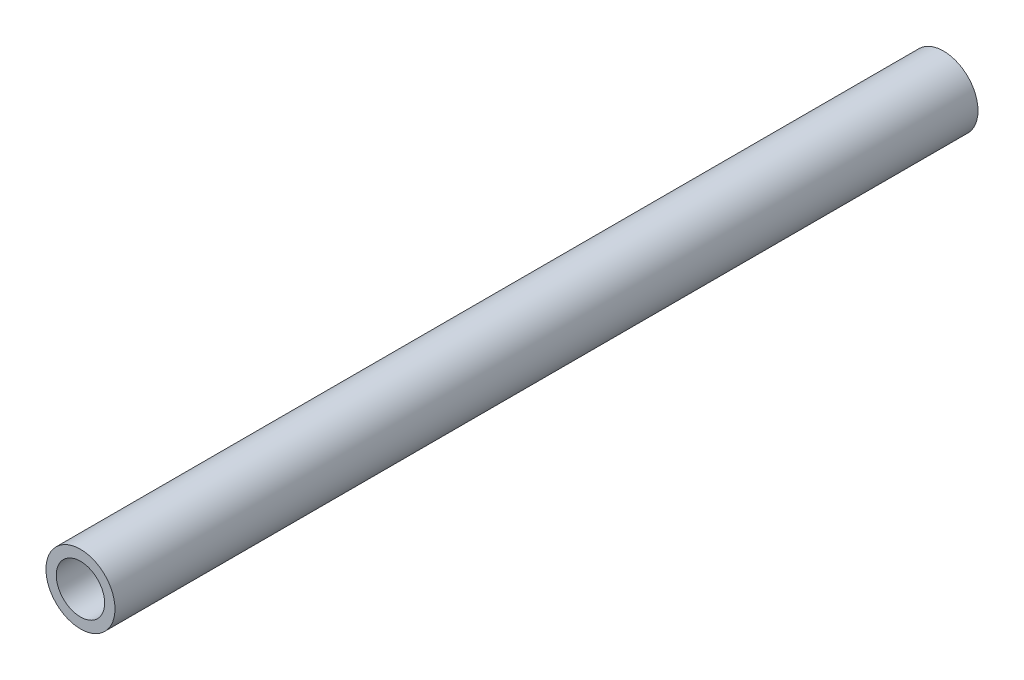
SolidWorks part; units mm, degrees
material "EM-CF"
ref_plane "Płaszczyzna przednia" through (0, 0, 0) normal (0, 0, 1) x (1, 0, 0)
ref_plane "Płaszczyzna górna" through (0, 0, 0) normal (0, 1, 0) x (1, 0, 0)
ref_plane "Płaszczyzna prawa" through (0, 0, 0) normal (1, 0, 0) x (0, 0, -1)
sketch "Szkic1" plane through (0, 0, 0) normal (0, 0, 1) x (1, 0, 0)
  circle A0 centre (0, 0) radius 7
  circle A1 centre (0, 0) radius 10
  dimension "D1" = 3
  dimension "D2" = 20
extrude "Dodanie-wyciągnięcie1" add sketch "Szkic1" along normal blind 250
